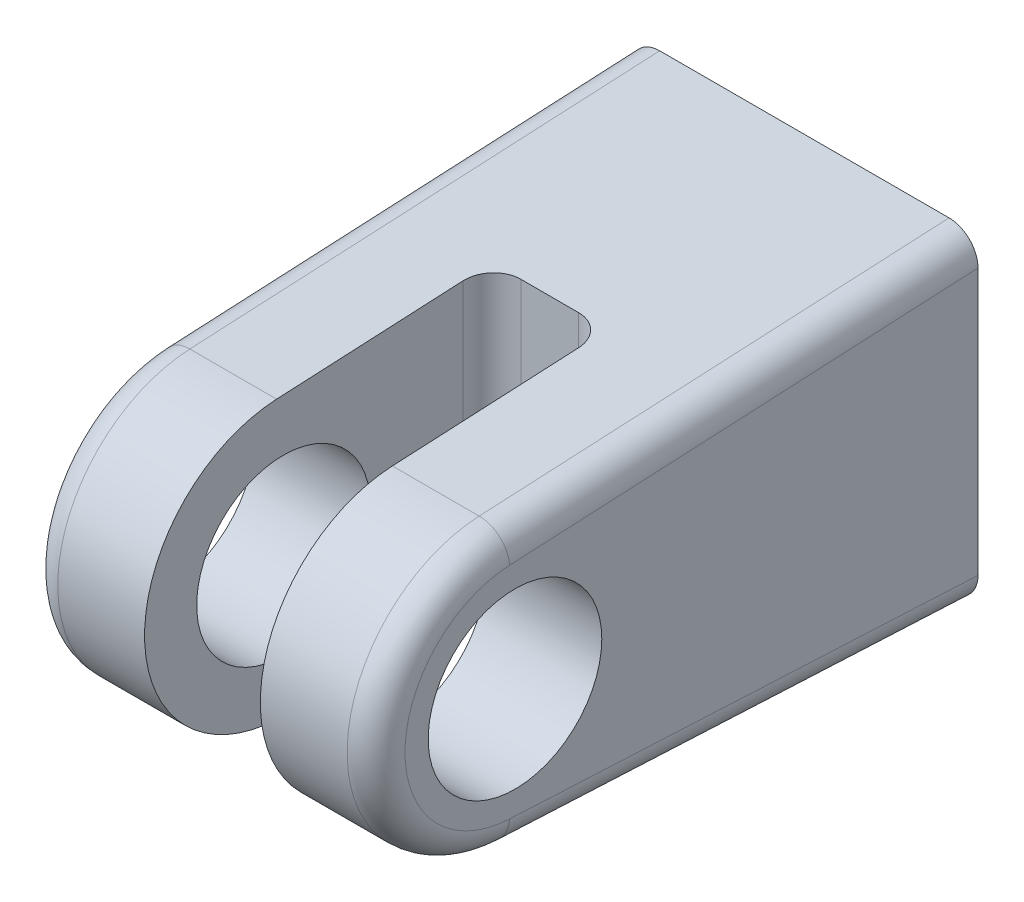
SolidWorks part; units mm, degrees
ref_plane "Front" through (0, 0, 0) normal (0, 0, 1) x (1, 0, 0)
ref_plane "Top" through (0, 0, 0) normal (0, 1, 0) x (1, 0, 0)
ref_plane "Right" through (0, 0, 0) normal (1, 0, 0) x (0, 0, -1)
sketch "Sketch2" plane through (0, 0, 0) normal (1, 0, 0) x (0, 0, -1)
  line L0 (0, 8.89) -> (-25.7777, 7.6106)
  line L1 (0, -8.89) -> (-25.7777, -7.6106)
  line L2 (0, 8.89) -> (0, -8.89)
  line L3 (0, 0) -> (-66.2459, 0) construction
  arc A0 (-25.7777, 7.6106) -> (-25.7777, -7.6106) centre (-25.4, 0) ccw
  dimension "D1" = 7.62
  dimension "D2" = 17.78
  dimension "D3" = 25.4
extrude "Extrude2" add sketch "Sketch2" along normal mid plane 19.05
sketch "Sketch3" plane through (0, 0, 0) normal (0, 1, 0) x (1, 0, 0)
  line L0 (0, -13.97) -> (0, 0) construction
  line L1 (-3.175, -13.97) -> (3.175, -13.97)
  line L2 (-3.175, -13.97) -> (-3.175, -33.02)
  line L3 (-3.175, -33.02) -> (3.175, -33.02)
  line L4 (3.175, -13.97) -> (3.175, -33.02)
  line L5 (-9.525, -33.02) -> (9.525, -33.02) construction
  dimension "D1" = 6.35
  dimension "D2" = 19.05
extrude "Cut-Extrude1" cut sketch "Sketch3" against normal through all and the other way through all
sketch "Sketch4" plane through (9.525, 0, 0) normal (1, 0, 0) x (0, 0, -1)
  circle A0 centre (-25.4, 0) radius 4.7625
  dimension "D1" = 9.525
extrude "Cut-Extrude2" cut sketch "Sketch4" against normal through all
sketch "Sketch5" plane through (0, 0, 0) normal (0, 0, -1) x (-1, 0, 0)
  circle A0 centre (0, 0) radius 6.35
  dimension "D1" = 12.7
extrude "Cut-Extrude3" cut sketch "Sketch5" against normal blind 9.525
fillet "Fillet1" radius 1.5875 8 edges at (-9.525, -8.2503, 12.8889) (-9.525, 0, 33.02) (9.525, -8.2503, 12.8889) (9.525, 0, 33.02) (-9.525, 8.2503, 12.8889) (9.525, 8.2503, 12.8889) (-3.175, 0, 13.97) (3.175, 0, 13.97)
